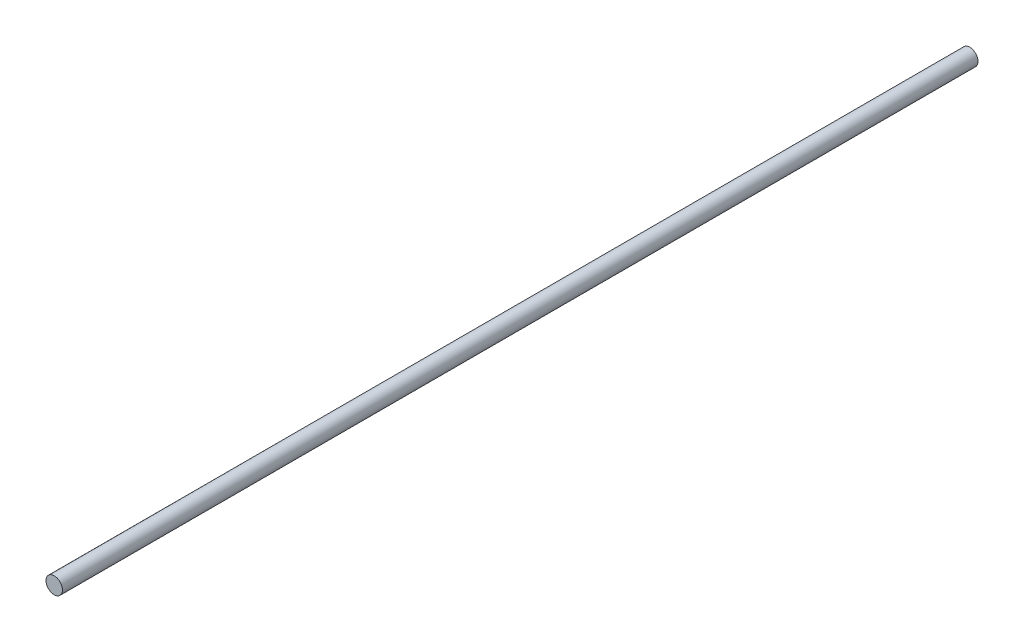
SolidWorks part; units mm, degrees
ref_plane "Front Plane" through (0, 0, 0) normal (0, 0, 1) x (1, 0, 0)
ref_plane "Top Plane" through (0, 0, 0) normal (0, 1, 0) x (1, 0, 0)
ref_plane "Right Plane" through (0, 0, 0) normal (1, 0, 0) x (0, 0, -1)
sketch "Sketch1" plane through (0, 0, 0) normal (0, 0, 1) x (1, 0, 0)
  circle A0 centre (0, 0) radius 4
  dimension "D1" = 8
extrude "Boss-Extrude1" add sketch "Sketch1" along normal blind 445
cosmetic thread "Cosmetic Thread1" parameters "D2"=6.891
